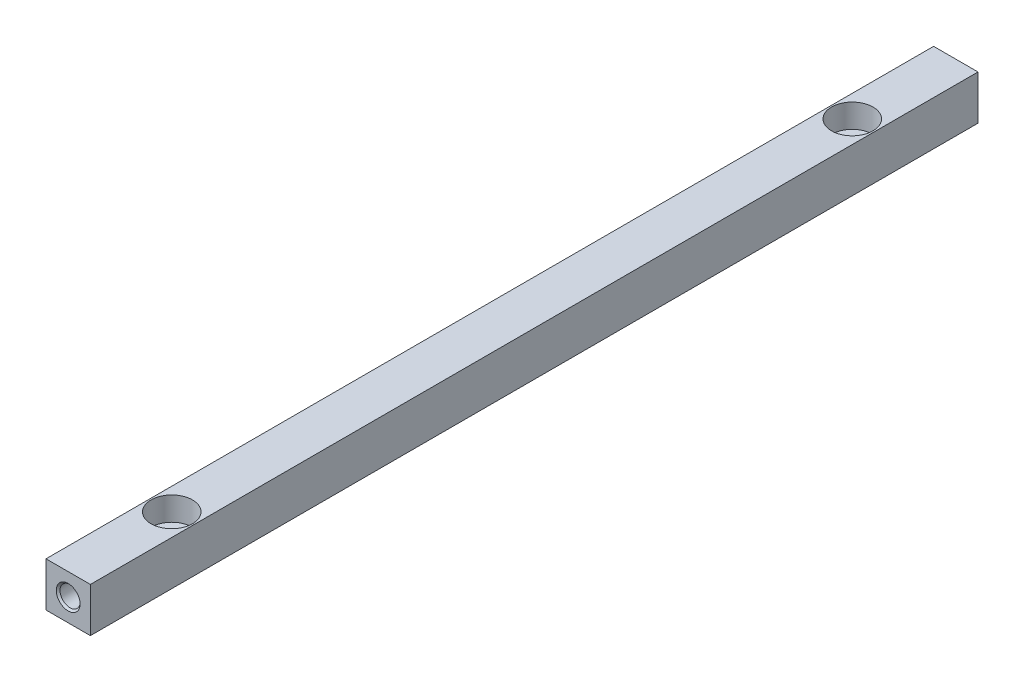
SolidWorks part; units mm, degrees
ref_plane "Ön Düzlem" through (0, 0, 0) normal (0, 0, 1) x (1, 0, 0)
ref_plane "Üst Düzlem" through (0, 0, 0) normal (0, 1, 0) x (1, 0, 0)
ref_plane "Sağ Düzlem" through (0, 0, 0) normal (1, 0, 0) x (0, 0, -1)
sketch "Sketch1" plane through (0, 0, 0) normal (0, 0, 1) x (1, 0, 0)
  line L1 (-7.5, -7.5) -> (7.5, -7.5)
  line L2 (-7.5, -7.5) -> (-7.5, 7.5)
  line L3 (-7.5, 7.5) -> (7.5, 7.5)
  line L4 (7.5, -7.5) -> (7.5, 7.5)
  line L5 (-7.5, -7.5) -> (7.5, 7.5) construction
  line L6 (-7.5, 7.5) -> (7.5, -7.5) construction
  point P0 (0, 0)
  dimension "D1" = 15
extrude "Boss-Extrude1" add sketch "Sketch1" along normal mid plane 300
hole_wizard "M8 Tapped Hole1" positions "Sketch2" profile "Sketch3" tap size "M8" standard "ISO"
sketch "Sketch2" plane through (0, 0, 150) normal (0, 0, 1) x (1, 0, 0)
  point P0 (0, 0)
sketch "Sketch3" plane through (0, 0, 150) normal (1, 0, 0) x (0, -1, 0)
  line L0 (0, 0) -> (0, 24.2929)
  line L1 (0, 24.2929) -> (3.4, 22.25)
  line L2 (3.4, 22.25) -> (3.4, 0.625)
  line L3 (3.4, 0.625) -> (4.025, 0)
  line L5 (4.025, 0) -> (0, 0)
  line L6 (-3.4, 0.625) -> (-4.025, 0) construction
  line L10 (0, 24.2929) -> (-3.4, 22.25) construction
  line L11 (0, -6.35) -> (0, 107.95) construction
  dimension "Tap Drill Dia." = 6.8
  dimension "Tap Drill Depth" = 22.25
  dimension "Near C'Sink Dia." = 8.05
  dimension "Near C'Sink Angle" = 90
  dimension "Drill Angle" = 118
cosmetic thread "Hole Thread1" parameters "D1"=16, "D2"=8
mirror "Mirror1" about plane through (0, 0, 0) normal (0, 0, 1) of "M8 Tapped Hole1"
cosmetic thread "Hole Thread2" parameters "D1"=16, "D2"=8
hole_wizard "Hole1" positions "Sketch4" profile "Sketch5" legacy
sketch "Sketch4" plane through (0, 7.5, 0) normal (0, 1, 0) x (1, 0, 0)
  line L0 (7.5, 150) -> (-7.5, 150) construction
  point P0 (0, 115)
  point P5 (0, 0)
  dimension "D1" = 35
sketch "Sketch5" plane through (0, 7.5, -115) normal (1, 0, 0) x (0, 0, 1)
  line L0 (0, 0) -> (0, 15)
  line L1 (0, 15) -> (4.25, 15)
  line L2 (4.25, 15) -> (4.25, 8)
  line L3 (4.25, 8) -> (7, 8)
  line L4 (7, 8) -> (7, 0)
  line L5 (7, 0) -> (0, 0)
  line L6 (0, 110) -> (0, -10) construction
  dimension "Diameter" = 8.5
  dimension "Depth" = 15
  dimension "C-Bore Diameter" = 14
  dimension "C-Bore Depth" = 8
mirror "Mirror2" about plane through (0, 0, 0) normal (0, 0, 1) of "Hole1"
